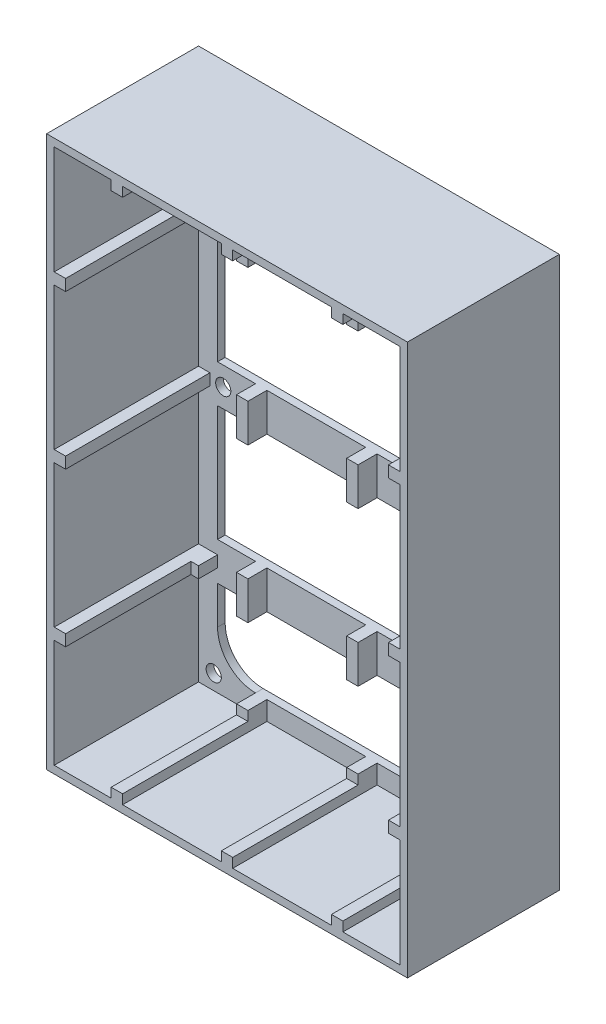
SolidWorks part; units mm, degrees
ref_plane "前视基准面" through (0, 0, 0) normal (0, 0, 1) x (1, 0, 0)
ref_plane "上视基准面" through (0, 0, 0) normal (0, 1, 0) x (1, 0, 0)
ref_plane "右视基准面" through (0, 0, 0) normal (1, 0, 0) x (0, 0, -1)
sketch "Sketch1" plane through (0, 0, 0) normal (0, 0, 1) x (1, 0, 0)
  line L1 (-47.5, 72.5) -> (47.5, 72.5)
  line L2 (-47.5, 72.5) -> (-47.5, -72.5)
  line L3 (-47.5, -72.5) -> (47.5, -72.5)
  line L4 (47.5, 72.5) -> (47.5, -72.5)
  line L5 (-47.5, 72.5) -> (47.5, -72.5) construction
  line L6 (-47.5, -72.5) -> (47.5, 72.5) construction
  point P0 (0, 0)
  dimension "D1" = 95
  dimension "D2" = 145
extrude "Boss-Extrude1" add sketch "Sketch1" along normal mid plane 40
sketch "Sketch2" plane through (0, 0, 20) normal (0, 0, 1) x (1, 0, 0)
  line L8 (45.5, -70.5) -> (45.5, 70.5)
  line L9 (45.5, 70.5) -> (-45.5, 70.5)
  line L10 (-45.5, 70.5) -> (-45.5, -70.5)
  line L11 (-45.5, -70.5) -> (45.5, -70.5)
  line L12 (45.5, -70.5) -> (45.5, 70.5)
  line L13 (45.5, 70.5) -> (-45.5, 70.5)
  line L14 (-45.5, 70.5) -> (-45.5, -70.5)
  line L15 (-45.5, -70.5) -> (45.5, -70.5)
  dimension "D1" = 2
extrude "Cut-Extrude1" cut sketch "Sketch2" against normal blind 40
ref_plane "Base" through (0, 0, -20) normal (0, 0, -1) x (-1, 0, 0)
sketch "Sketch3" plane through (0, 0, -20) normal (0, 0, -1) x (-1, 0, 0)
  line L0 (-45.5, 70.5) -> (45.5, 70.5) construction
  line L2 (42.5, -70.5) -> (42.5, 70.5) construction
  line L4 (-42.5, -70.5) -> (-42.5, 70.5) construction
  line L5 (42.5, -70.5) -> (-42.5, 70.5) construction
  line L6 (42.5, 70.5) -> (-42.5, -70.5) construction
  line L7 (-40.5, -35.5) -> (40.5, -35.5)
  line L8 (-40.5, -45.5) -> (40.5, -45.5)
  line L9 (-40.5, 5) -> (40.5, 5)
  line L10 (-40.5, -5) -> (40.5, -5)
  line L11 (45.5, -70.5) -> (-45.5, -70.5) construction
  line L12 (45.5, 70.5) -> (45.5, -70.5) construction
  line L13 (-45.5, -70.5) -> (-45.5, 70.5) construction
  line L14 (45.5, -70.5) -> (-45.5, -70.5)
  line L15 (-40.5, -65.5) -> (40.5, -65.5)
  line L16 (40.5, 65.5) -> (-40.5, 65.5)
  line L17 (40.5, -65.5) -> (40.5, 65.5)
  line L18 (-40.5, 65.5) -> (-40.5, -65.5)
  line L19 (-30.5, -65.5) -> (30.5, -65.5)
  line L20 (30.5, 65.5) -> (-30.5, 65.5)
  line L21 (40.5, -55.5) -> (40.5, -45.5)
  line L22 (-40.5, 55.5) -> (-40.5, 45.5)
  line L23 (45.5, 70.5) -> (45.5, -70.5)
  line L24 (-45.5, -70.5) -> (-45.5, 70.5)
  line L25 (-45.5, 70.5) -> (45.5, 70.5)
  line L26 (-40.5, 45.5) -> (40.5, 45.5)
  line L27 (-40.5, 35.5) -> (40.5, 35.5)
  line L28 (-62.7216, 0) -> (91.8842, 0) construction
  line L29 (-40.5, 35.5) -> (-40.5, 5)
  line L30 (40.5, 45.5) -> (40.5, 55.5)
  line L31 (40.5, 5) -> (40.5, 35.5)
  line L32 (-40.5, -5) -> (-40.5, -35.5)
  line L33 (-40.5, -45.5) -> (-40.5, -55.5)
  line L34 (40.5, -35.5) -> (40.5, -5)
  arc A0 (-30.5, -65.5) -> (-40.5, -55.5) centre (-30.5, -55.5) cw
  arc A1 (30.5, -65.5) -> (40.5, -55.5) centre (30.5, -55.5) ccw
  arc A2 (30.5, 65.5) -> (40.5, 55.5) centre (30.5, 55.5) cw
  arc A3 (-30.5, 65.5) -> (-40.5, 55.5) centre (-30.5, 55.5) ccw
  point P0 (0, 0)
  dimension "D3" = 10
  dimension "D1" = 85
  dimension "D4" = 10
  dimension "D5" = 20
  dimension "D6" = 5
  dimension "D2" = 5
extrude "Boss-Extrude2" add sketch "Sketch3" against normal blind 2
sketch "Sketch4" plane through (0, 0, -20) normal (0, 0, -1) x (-1, 0, 0)
  line L0 (-47.5, 72.5) -> (47.5, 72.5) construction
  line L1 (-47.5, -72.5) -> (-47.5, 72.5) construction
  line L2 (47.5, 72.5) -> (47.5, -72.5) construction
  line L3 (-75.8795, 0) -> (73.4613, 0) construction
  circle A0 centre (-41.5, 66.5) radius 2
  circle A1 centre (41.5, 66.5) radius 2
  circle A2 centre (41.5, -66.5) radius 2
  circle A3 centre (-41.5, -66.5) radius 2
  circle A4 centre (-39, 0) radius 2
  circle A5 centre (39, 0) radius 2
  dimension "D1" = 6
  dimension "D2" = 6
  dimension "D3" = 6
  dimension "D4" = 6
extrude "Cut-Extrude2" cut sketch "Sketch4" against normal up to next
sketch "Sketch6" plane through (0, 0, -18) normal (0, 0, 1) x (1, 0, 0)
  line L0 (-45.5, 70.5) -> (45.5, 70.5) construction
  line L1 (42.5, -68) -> (-42.5, -68) construction
  line L2 (42.5, -68) -> (42.5, 68) construction
  line L3 (42.5, 68) -> (-42.5, 68) construction
  line L4 (-42.5, -68) -> (-42.5, 68) construction
  line L5 (-30.5, 65.5) -> (30.5, 65.5) construction
  line L6 (-30.5, 68) -> (-27.5, 68)
  line L7 (-30.5, 70.5) -> (-27.5, 70.5)
  line L8 (-30.5, 70.5) -> (-30.5, 68)
  line L9 (-30.5, 68) -> (-27.5, 68)
  line L10 (-27.5, 70.5) -> (-27.5, 68)
  line L11 (0, 86.8311) -> (0, -114.9189) construction
  line L12 (-76.1678, 0) -> (120.2613, 0) construction
  line L13 (30.5, 68) -> (27.5, 68)
  line L14 (27.5, 70.5) -> (27.5, 68)
  line L15 (30.5, 70.5) -> (27.5, 70.5)
  line L16 (30.5, 70.5) -> (30.5, 68)
  line L17 (30.5, -70.5) -> (30.5, -68)
  line L18 (-1.5, 70.5) -> (1.5, 70.5)
  line L19 (-1.5, 70.5) -> (-1.5, 68)
  line L20 (-1.5, 68) -> (1.5, 68)
  line L21 (1.5, 70.5) -> (1.5, 68)
  line L22 (30.5, -70.5) -> (27.5, -70.5)
  line L23 (27.5, -70.5) -> (27.5, -68)
  line L24 (30.5, -68) -> (27.5, -68)
  line L25 (-1.5, -68) -> (1.5, -68)
  line L26 (1.5, -70.5) -> (1.5, -68)
  line L27 (-1.5, -70.5) -> (1.5, -70.5)
  line L28 (-1.5, -70.5) -> (-1.5, -68)
  line L29 (-30.5, -68) -> (-27.5, -68)
  line L30 (-27.5, -70.5) -> (-27.5, -68)
  line L31 (-30.5, -70.5) -> (-27.5, -70.5)
  line L32 (-30.5, -70.5) -> (-30.5, -68)
  line L33 (-45.5, 70.5) -> (-45.5, -70.5) construction
  line L34 (-45.5, 42) -> (-42.5, 42)
  line L35 (-45.5, 42) -> (-45.5, 39)
  line L36 (-45.5, 39) -> (-42.5, 39)
  line L37 (-42.5, 42) -> (-42.5, 39)
  line L38 (-45.5, -70.5) -> (-45.5, 70.5) construction
  line L39 (-45.5, 1.5) -> (-42.5, 1.5)
  line L40 (-45.5, 1.5) -> (-45.5, -1.5)
  line L41 (-45.5, -1.5) -> (-42.5, -1.5)
  line L42 (-42.5, 1.5) -> (-42.5, -1.5)
  line L43 (-33.759, -35.5) -> (-33.759, -45.5) construction
  line L44 (-45.5, -39) -> (-42.5, -39)
  line L45 (-45.5, -39) -> (-45.5, -42)
  line L46 (-45.5, -42) -> (-42.5, -42)
  line L47 (-42.5, -39) -> (-42.5, -42)
  line L48 (40.5, -35.5) -> (-40.5, -35.5) construction
  line L49 (-40.5, -45.5) -> (40.5, -45.5) construction
  line L50 (-33.759, 5) -> (-33.759, -5) construction
  line L51 (40.5, 5) -> (-40.5, 5) construction
  line L52 (-40.5, -5) -> (40.5, -5) construction
  line L53 (-34.8742, 45.5) -> (-34.8742, 35.5) construction
  line L54 (40.5, 45.5) -> (-40.5, 45.5) construction
  line L55 (-40.5, 35.5) -> (40.5, 35.5) construction
  line L56 (45.5, 39) -> (42.5, 39)
  line L57 (42.5, 42) -> (42.5, 39)
  line L58 (45.5, 42) -> (42.5, 42)
  line L59 (45.5, 42) -> (45.5, 39)
  line L60 (45.5, -1.5) -> (42.5, -1.5)
  line L61 (42.5, 1.5) -> (42.5, -1.5)
  line L62 (45.5, 1.5) -> (42.5, 1.5)
  line L63 (45.5, 1.5) -> (45.5, -1.5)
  line L64 (45.5, -42) -> (42.5, -42)
  line L65 (42.5, -39) -> (42.5, -42)
  line L66 (45.5, -39) -> (42.5, -39)
  line L67 (45.5, -39) -> (45.5, -42)
  line L68 (-30.5, 45.5) -> (-30.5, 35.5)
  line L69 (-30.5, 35.5) -> (-27.5, 35.5)
  line L70 (-27.5, 35.5) -> (-27.5, 45.5)
  line L71 (-27.5, 45.5) -> (-30.5, 45.5)
  line L72 (-30.5, 68) -> (-30.5, 65.5)
  line L73 (-1.5, 45.5) -> (1.5, 45.5)
  line L74 (-1.5, 45.5) -> (-1.5, 35.5)
  line L75 (-1.5, 35.5) -> (1.5, 35.5)
  line L76 (1.5, 45.5) -> (1.5, 35.5)
  line L77 (27.5, 45.5) -> (30.5, 45.5)
  line L78 (27.5, 45.5) -> (27.5, 35.5)
  line L79 (27.5, 35.5) -> (30.5, 35.5)
  line L80 (30.5, 45.5) -> (30.5, 35.5)
  line L81 (-30.5, 5) -> (-27.5, 5)
  line L82 (-30.5, 5) -> (-30.5, -5)
  line L83 (-30.5, -5) -> (-27.5, -5)
  line L84 (-27.5, 5) -> (-27.5, -5)
  line L85 (-1.5, 5) -> (1.5, 5)
  line L86 (-1.5, 5) -> (-1.5, -5)
  line L87 (-1.5, -5) -> (1.5, -5)
  line L88 (1.5, 5) -> (1.5, -5)
  line L89 (27.5, 5) -> (30.5, 5)
  line L90 (27.5, 5) -> (27.5, -5)
  line L91 (27.5, -5) -> (30.5, -5)
  line L92 (30.5, 5) -> (30.5, -5)
  line L93 (-30.5, -35.5) -> (-27.5, -35.5)
  line L94 (-30.5, -35.5) -> (-30.5, -45.5)
  line L95 (-30.5, -45.5) -> (-27.5, -45.5)
  line L96 (-27.5, -35.5) -> (-27.5, -45.5)
  line L97 (-1.5, -35.5) -> (1.5, -35.5)
  line L98 (-1.5, -35.5) -> (-1.5, -45.5)
  line L99 (-1.5, -45.5) -> (1.5, -45.5)
  line L100 (1.5, -35.5) -> (1.5, -45.5)
  line L101 (27.5, -35.5) -> (30.5, -35.5)
  line L102 (27.5, -35.5) -> (27.5, -45.5)
  line L103 (27.5, -45.5) -> (30.5, -45.5)
  line L104 (30.5, -35.5) -> (30.5, -45.5)
  line L105 (-30.5, 65.5) -> (-27.5, 65.5)
  line L106 (-27.5, 68) -> (-27.5, 65.5)
  line L107 (30.5, -65.5) -> (-30.5, -65.5) construction
  line L108 (-1.5, 68) -> (1.5, 68)
  line L109 (-1.5, 68) -> (-1.5, 65.5)
  line L110 (-1.5, 65.5) -> (1.5, 65.5)
  line L111 (1.5, 68) -> (1.5, 65.5)
  line L112 (27.5, 68) -> (30.5, 68)
  line L113 (27.5, 68) -> (27.5, 65.5)
  line L114 (27.5, 65.5) -> (30.5, 65.5)
  line L115 (30.5, 68) -> (30.5, 65.5)
  line L116 (-42.5, 42) -> (-40.5, 42)
  line L117 (-42.5, 42) -> (-42.5, 39)
  line L118 (-42.5, 39) -> (-40.5, 39)
  line L119 (-40.5, 42) -> (-40.5, 39)
  line L120 (42.5, 42) -> (40.5, 42)
  line L121 (42.5, 42) -> (42.5, 39)
  line L122 (42.5, 39) -> (40.5, 39)
  line L123 (40.5, 42) -> (40.5, 39)
  line L124 (-42.5, -39) -> (-40.5, -39)
  line L125 (-42.5, -39) -> (-42.5, -42)
  line L126 (-42.5, -42) -> (-40.5, -42)
  line L127 (-40.5, -39) -> (-40.5, -42)
  line L128 (42.5, -39) -> (40.5, -39)
  line L129 (42.5, -39) -> (42.5, -42)
  line L130 (42.5, -42) -> (40.5, -42)
  line L131 (40.5, -39) -> (40.5, -42)
  line L132 (30.5, -68) -> (27.5, -68)
  line L133 (30.5, -68) -> (30.5, -65.5)
  line L134 (30.5, -65.5) -> (27.5, -65.5)
  line L135 (27.5, -68) -> (27.5, -65.5)
  line L137 (1.5, -68) -> (-1.5, -68)
  line L138 (1.5, -68) -> (1.5, -65.5)
  line L139 (1.5, -65.5) -> (-1.5, -65.5)
  line L140 (-1.5, -68) -> (-1.5, -65.5)
  line L141 (-30.5, -68) -> (-27.5, -68)
  line L142 (-30.5, -68) -> (-30.5, -65.5)
  line L143 (-30.5, -65.5) -> (-27.5, -65.5)
  line L144 (-27.5, -68) -> (-27.5, -65.5)
  point P0 (0, 0)
  point P70 (-34.8742, 40.5)
  point P71 (-33.759, -40.5)
  line M9 (40.5, -35.5) -> (-40.5, -35.5)
  line M11 (-40.5, -5) -> (40.5, -5)
  line M13 (40.5, 5) -> (-40.5, 5)
  line M15 (-40.5, 35.5) -> (40.5, 35.5)
  line M17 (-30.5, 65.5) -> (30.5, 65.5)
  line M20 (40.5, 45.5) -> (-40.5, 45.5)
  line M23 (30.5, -65.5) -> (-30.5, -65.5)
  line M26 (-40.5, -45.5) -> (40.5, -45.5)
  line M28 (-45.5, 70.5) -> (-45.5, -70.5)
  line M29 (-45.5, -70.5) -> (45.5, -70.5)
  line M30 (45.5, -70.5) -> (45.5, 70.5)
  line M31 (45.5, 70.5) -> (-45.5, 70.5)
  dimension "D1" = 85
  dimension "D2" = 136
  dimension "D3" = 3
  dimension "D4" = 3
  dimension "D5" = 1.5
  dimension "D6" = 3
  dimension "D7" = 3
  dimension "D8" = 3
  dimension "D9" = 1.5
  dimension "D10" = 1.5
  dimension "D11" = 1.5
extrude "Boss-Extrude3" add sketch "Sketch6" along normal blind 5 contours L10 L8 L6 M31 | L106 L6 L72 M17 | L111 L20 L109 M17 | L21 L19 L20 M31 | L16 L14 L13 M31 | L115 L13 L113 M17 | L58 L57 L56 M30 | L120 L123 L122 L57 | L80 L78 M20 M15 | L70 L68 M15 M20 | L37 L34 L36 M28 | L119 L116 L37 L118 | L62 L61 L60 M30 | L92 L90 M13 M11 | L84 L82 M13 M11 | L42 L39 L41 M28 | L47 L44 L46 M28 | L127 L124 L47 L126 | L96 L94 M9 M26 | L104 L102 M9 M26 | L128 L131 L130 L65 | L66 L65 L64 M30 | L32 L30 L29 M29 | L29 L144 L142 M23 | L140 L25 L138 M23 | L28 L26 L25 M29 | L17 L24 L23 M29 | L135 L24 L133 M23 | L74 L75 L76 L73 | L88 L87 L86 L85 | L100 L99 L98 L97
sketch "Sketch7" plane through (0, 0, -13) normal (0, 0, 1) x (1, 0, 0)
  line L0 (-45.5, 1.5) -> (-45.5, -1.5) construction
  line L1 (-45.5, -1.5) -> (-42.5, -1.5) construction
  line L2 (-42.5, -1.5) -> (-42.5, 1.5) construction
  line L3 (-42.5, 1.5) -> (-45.5, 1.5) construction
  line L4 (-45.5, 42) -> (-45.5, 39)
  line L5 (-45.5, 39) -> (-42.5, 39)
  line L6 (-42.5, 39) -> (-42.5, 42)
  line L7 (-42.5, 42) -> (-45.5, 42)
  line L8 (-45.5, 42) -> (-45.5, 39)
  line L9 (-45.5, 39) -> (-42.5, 39)
  line L10 (-42.5, 39) -> (-42.5, 42)
  line L11 (-42.5, 42) -> (-45.5, 42)
  line L12 (-27.5, 70.5) -> (-27.5, 65.5) construction
  line L14 (-27.5, 68) -> (-30.5, 68)
  line L20 (-45.5, -39) -> (-45.5, -42) construction
  line L21 (-45.5, -42) -> (-42.5, -42) construction
  line L22 (-42.5, -42) -> (-42.5, -39) construction
  line L23 (-42.5, -39) -> (-45.5, -39) construction
  line L24 (-30.5, -68) -> (-30.5, -70.5) construction
  line L25 (-30.5, -70.5) -> (-27.5, -70.5) construction
  line L26 (-27.5, -70.5) -> (-27.5, -68) construction
  line L27 (-27.5, -68) -> (-30.5, -68) construction
  line L28 (-1.5, -68) -> (-1.5, -70.5) construction
  line L29 (-1.5, -70.5) -> (1.5, -70.5) construction
  line L30 (1.5, -70.5) -> (1.5, -68) construction
  line L31 (1.5, -68) -> (-1.5, -68) construction
  line L32 (27.5, -70.5) -> (30.5, -70.5) construction
  line L33 (30.5, -70.5) -> (30.5, -68) construction
  line L34 (30.5, -68) -> (27.5, -68) construction
  line L35 (27.5, -68) -> (27.5, -70.5) construction
  line L36 (45.5, -42) -> (45.5, -39) construction
  line L37 (45.5, -39) -> (42.5, -39) construction
  line L38 (42.5, -39) -> (42.5, -42) construction
  line L39 (42.5, -42) -> (45.5, -42) construction
  line L40 (45.5, -1.5) -> (45.5, 1.5) construction
  line L41 (45.5, 1.5) -> (42.5, 1.5) construction
  line L42 (42.5, 1.5) -> (42.5, -1.5) construction
  line L43 (42.5, -1.5) -> (45.5, -1.5) construction
  line L44 (45.5, 39) -> (45.5, 42) construction
  line L45 (45.5, 42) -> (42.5, 42) construction
  line L46 (42.5, 42) -> (42.5, 39) construction
  line L47 (42.5, 39) -> (45.5, 39) construction
  line L48 (30.5, 68) -> (30.5, 70.5) construction
  line L49 (30.5, 70.5) -> (27.5, 70.5) construction
  line L50 (27.5, 70.5) -> (27.5, 68) construction
  line L51 (27.5, 68) -> (30.5, 68) construction
  line L52 (-1.5, 70.5) -> (-1.5, 68) construction
  line L53 (-1.5, 68) -> (1.5, 68) construction
  line L54 (1.5, 68) -> (1.5, 70.5) construction
  line L55 (1.5, 70.5) -> (-1.5, 70.5) construction
  line L56 (-45.5, 1.5) -> (-45.5, -1.5)
  line L57 (-45.5, -1.5) -> (-42.5, -1.5)
  line L58 (-42.5, -1.5) -> (-42.5, 1.5)
  line L59 (-42.5, 1.5) -> (-45.5, 1.5)
  line L60 (-45.5, -39) -> (-45.5, -42)
  line L61 (-45.5, -42) -> (-42.5, -42)
  line L62 (-42.5, -42) -> (-42.5, -39)
  line L63 (-42.5, -39) -> (-45.5, -39)
  line L64 (-30.5, -68) -> (-30.5, -70.5)
  line L65 (-30.5, -70.5) -> (-27.5, -70.5)
  line L66 (-27.5, -70.5) -> (-27.5, -68)
  line L67 (-27.5, -68) -> (-30.5, -68)
  line L68 (-1.5, -68) -> (-1.5, -70.5)
  line L69 (-1.5, -70.5) -> (1.5, -70.5)
  line L70 (1.5, -70.5) -> (1.5, -68)
  line L71 (1.5, -68) -> (-1.5, -68)
  line L72 (27.5, -70.5) -> (30.5, -70.5)
  line L73 (30.5, -70.5) -> (30.5, -68)
  line L74 (30.5, -68) -> (27.5, -68)
  line L75 (27.5, -68) -> (27.5, -70.5)
  line L76 (45.5, -42) -> (45.5, -39)
  line L77 (45.5, -39) -> (42.5, -39)
  line L78 (42.5, -39) -> (42.5, -42)
  line L79 (42.5, -42) -> (45.5, -42)
  line L80 (45.5, -1.5) -> (45.5, 1.5)
  line L81 (45.5, 1.5) -> (42.5, 1.5)
  line L82 (42.5, 1.5) -> (42.5, -1.5)
  line L83 (42.5, -1.5) -> (45.5, -1.5)
  line L84 (45.5, 39) -> (45.5, 42)
  line L85 (45.5, 42) -> (42.5, 42)
  line L86 (42.5, 42) -> (42.5, 39)
  line L87 (42.5, 39) -> (45.5, 39)
  line L88 (30.5, 68) -> (30.5, 70.5)
  line L89 (30.5, 70.5) -> (27.5, 70.5)
  line L90 (27.5, 70.5) -> (27.5, 68)
  line L91 (27.5, 68) -> (30.5, 68)
  line L92 (-1.5, 70.5) -> (-1.5, 68)
  line L93 (-1.5, 68) -> (1.5, 68)
  line L94 (1.5, 68) -> (1.5, 70.5)
  line L95 (1.5, 70.5) -> (-1.5, 70.5)
  line L96 (-27.5, 68) -> (-27.5, 70.5)
  line L97 (-27.5, 70.5) -> (-30.5, 70.5)
  line L98 (-30.5, 68) -> (-30.5, 70.5)
  dimension "D1" = 0
extrude "Boss-Extrude4" add sketch "Sketch7" along normal up to surface (33 mm away) up to face at (0, 0, 20)
